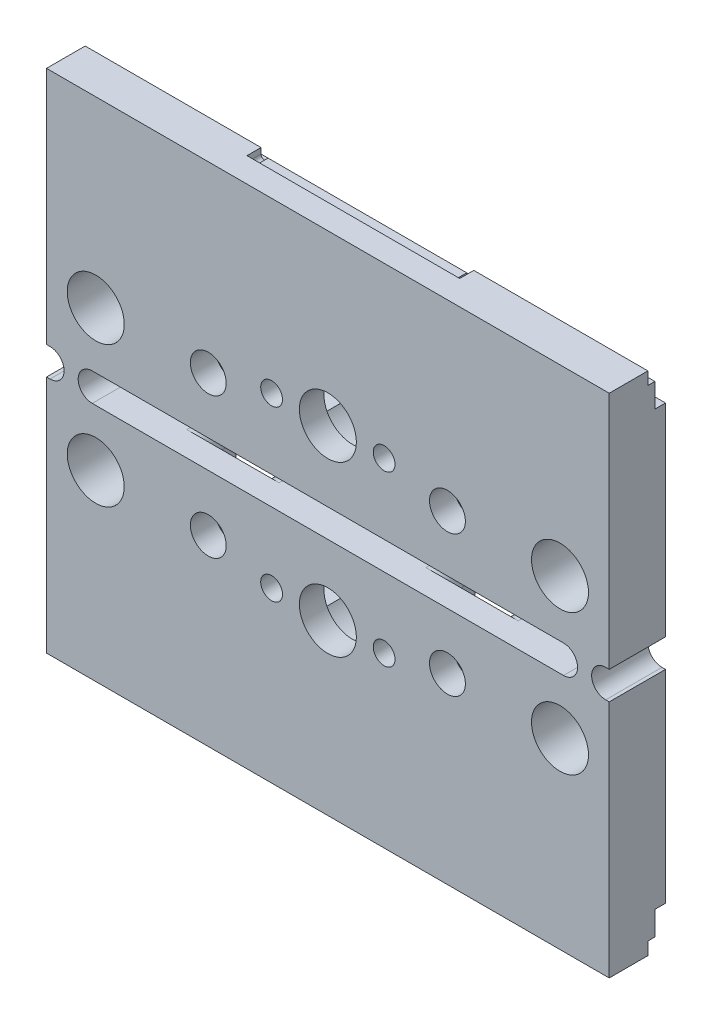
SolidWorks part; units mm, degrees
ref_plane "前视基准面" through (0, 0, 0) normal (0, 0, 1) x (1, 0, 0)
ref_plane "上视基准面" through (0, 0, 0) normal (0, 1, 0) x (1, 0, 0)
ref_plane "右视基准面" through (0, 0, 0) normal (1, 0, 0) x (0, 0, -1)
sketch "前视图草图" plane through (0, 0, 0) normal (0, 0, 1) x (1, 0, 0)
  line L0 (0, 0) -> (8.5179, 0) construction
  line L1 (0, 0) -> (0, 5.4227) construction
sketch "草图2" plane through (0, 0, 0) normal (0, 0, 1) x (1, 0, 0)
  line L0 (0, 0) -> (80, 0)
  line L1 (-200000, 0) -> (200008.5179, 0) construction
  line L2 (80, 0) -> (80, 34)
  line L3 (80, 34) -> (0, 34)
  line L4 (0, -200000) -> (0, 200005.4227) construction
  line L5 (0, 34) -> (0, 0)
  circle A0 centre (7, 8) radius 4.05
  circle A1 centre (40, 10) radius 4.05
  circle A2 centre (73, 8) radius 4.05
  dimension "D3" = 8
  dimension "D5" = 10
  dimension "D9" = 8.1
  dimension "D10" = 8.1
  dimension "D11" = 8.1
  dimension "D1" = 34
  dimension "D2" = 80
  dimension "D4" = 7
  dimension "D6" = 7
  dimension "D7" = 8
  dimension "D8" = 40
extrude "凸台-拉伸1" add sketch "草图2" along normal blind 8
sketch "草图3" plane through (0, 0, 8) normal (0, 0, 1) x (1, 0, 0)
  line L0 (16.088, 8) -> (31.4805, 8) construction
  line L1 (7, 8) -> (7, 16.8386) construction
  line L2 (73, 8) -> (73, 16.5917) construction
  line L4 (-200000, 0) -> (200008.5179, 0) construction
  circle A2 centre (23, 8) radius 2.55
  circle A3 centre (57, 8) radius 2.55
  dimension "D4" = 5.1
  dimension "D5" = 5.1
  dimension "D1" = 8
  dimension "D2" = 16
  dimension "D3" = 16
extrude "切除-拉伸1" cut sketch "草图3" against normal through all
sketch "草图4" plane through (80, 0, 0) normal (1, 0, 0) x (0, 0, -1)
  line L1 (0, -200000) -> (0, 200005.4227) construction
  line L2 (-1.5, 32.2) -> (-2.5, 32.2)
  line L3 (-2.5, 32.2) -> (-2.5, 34)
  line L4 (-8, 34) -> (0, 34) construction
  line L5 (-2.5, 34) -> (0, 34)
  line L6 (-1.5, 32.2) -> (-1.5, 28.8)
  line L7 (-1.5, 28.8) -> (0, 28.8)
  line L8 (0, 28.8) -> (0, 34)
  dimension "D1" = 3.4
  dimension "D2" = 2.5
  dimension "D3" = 1.5
  dimension "D4" = 1.8
extrude "切除-拉伸2" cut sketch "草图4" against normal through all
sketch "草图5" plane through (0, 0, 8) normal (0, 0, 1) x (1, 0, 0)
  line L0 (40, 10) -> (56.5376, 10) construction
  circle A0 centre (40, 10) radius 8 construction
  circle A1 centre (48, 10) radius 1.55
  circle A2 centre (32, 10) radius 1.55
  dimension "D1" = 3.1
  dimension "D2" = 3.1
  dimension "D3" = 16
extrude "切除-拉伸3" cut sketch "草图5" against normal through all
sketch "草图7" plane through (0, 0, 0) normal (0, 0, -1) x (-1, 0, 0)
  line L0 (-40, 12) -> (-40, -8.3696) construction
  line L1 (-23, 10) -> (-23, -2.3368) construction
  line L2 (200000, 0) -> (-200008.5179, 0) construction
  line L6 (-27.05, 10) -> (-27.05, 2.5)
  line L7 (-29.55, 0) -> (-16.45, 0)
  line L8 (-18.95, 2.5) -> (-18.95, 10)
  line L9 (-23, 8) -> (-23, 15.9045) construction
  line L13 (0, -200000) -> (0, 200005.4227) construction
  line L14 (-57, 8) -> (-57, 15.9045) construction
  line L15 (-57, 10) -> (-57, -2.3368) construction
  line L16 (-61.05, 2.5) -> (-61.05, 10)
  line L17 (-50.45, 0) -> (-63.55, 0)
  line L18 (-52.95, 10) -> (-52.95, 2.5)
  arc A1 (-18.95, 10) -> (-27.05, 10) centre (-23, 10) ccw
  arc A4 (-29.55, 0) -> (-27.05, 2.5) centre (-29.55, 2.5) ccw
  arc A5 (-18.95, 2.5) -> (-16.45, 0) centre (-16.45, 2.5) ccw
  arc A7 (-61.05, 2.5) -> (-63.55, 0) centre (-63.55, 2.5) cw
  arc A8 (-50.45, 0) -> (-52.95, 2.5) centre (-50.45, 2.5) cw
  arc A9 (-61.05, 10) -> (-52.95, 10) centre (-57, 10) cw
  dimension "D1" = 40
  dimension "D4" = 8.1
  dimension "D7" = 2.5
  dimension "D8" = 2.5
  dimension "D3" = 10
extrude "切除-拉伸4" cut sketch "草图7" against normal blind 4.5
sketch "草图8" plane through (0, 0, 0) normal (0, 0, -1) x (-1, 0, 0)
  line L0 (-40, 10) -> (-57.3165, 10) construction
  line L1 (-40, 20) -> (-40, 35.6562) construction
  line L2 (-30.5, 12.85) -> (-49.5, 12.85)
  line L3 (-49.5, 7.15) -> (-30.5, 7.15)
  line L4 (200000, 0) -> (-200008.5179, 0) construction
  arc A0 (-30.5, 7.15) -> (-30.5, 12.85) centre (-30.5, 10) ccw
  arc A1 (-49.5, 12.85) -> (-49.5, 7.15) centre (-49.5, 10) ccw
  dimension "D1" = 5.7
  dimension "D2" = 9.5
  dimension "D3" = 9.5
  dimension "D4" = 10
extrude "切除-拉伸5" cut sketch "草图8" against normal blind 4.5
sketch "草图20" plane through (0, 0, 0) normal (0, 0, -1) x (-1, 0, 0)
  circle A0 centre (-40, 10) radius 5.5
  dimension "D1" = 11
extrude "切除-拉伸12" cut sketch "草图20" against normal blind 4.5
sketch "草图19" plane through (0, 0, 2.5) normal (0, 0, -1) x (-1, 0, 0)
  line L0 (0, 34) -> (-80, 34) construction
  line L1 (-25, 34) -> (-55.2479, 34)
  line L2 (-25, 34) -> (-25, 33.2)
  line L3 (-26, 33.2) -> (-54.2479, 33.2)
  line L4 (-55.2479, 34) -> (-55.2479, 33.2)
  line L5 (0, -200000) -> (0, 200005.4227) construction
  line L7 (0, 32.2) -> (-80, 32.2) construction
  line L8 (-56.3335, 32.7) -> (-52.9089, 32.7) construction
  line L9 (-55.2479, 1028.5823) -> (-55.2479, 33.2) construction
  line L10 (-25, 1028.5823) -> (-25, 32.7) construction
  line L11 (-55.2479, 32.7) -> (-55.2479, -973.3) construction
  line L12 (-25, 32.7) -> (-25, -973.3) construction
  arc A3 (-55.2479, 33.2) -> (-54.2479, 33.2) centre (-54.7479, 33.2) ccw
  arc A6 (-26, 33.2) -> (-25, 33.2) centre (-25.5, 33.2) ccw
  dimension "D3" = 1
  dimension "D4" = 1
  dimension "D2" = 0.8
  dimension "D1" = 0.5
  dimension "D9" = 25
extrude "切除-拉伸11" cut sketch "草图19" against normal blind 2
sketch "草图22" plane through (0, 0, 8) normal (0, 0, 1) x (1, 0, 0)
  line L1 (0, -200000) -> (0, 200005.4227) construction
  line L2 (0.5, -4) -> (6.5, -4)
  line L4 (79.5, 0) -> (73.5, 0)
  line L5 (4.5, 1.9875) -> (4.5, -4.1402) construction
  line L6 (75.5, -11.5647) -> (75.5, -5.1636) construction
  line L7 (80, 0) -> (80, 34) construction
  line L8 (73.5, -4) -> (79.5, -4)
  line L9 (6.5, 0) -> (0.5, 0)
  line L10 (77.5, -2.9635) -> (77.5, -4.3032) construction
  line L11 (2.5, -8.393) -> (2.5, -15.1693) construction
  arc A0 (6.5, 0) -> (6.5, -4) centre (6.5, -2) ccw
  arc A1 (73.5, -4) -> (73.5, 0) centre (73.5, -2) ccw
  arc A2 (0.5, -4) -> (0.5, 0) centre (0.5, -2) ccw
  arc A3 (79.5, 0) -> (79.5, -4) centre (79.5, -2) ccw
  dimension "D1" = 4.5
  dimension "D2" = 4.5
  dimension "D3" = 4
  dimension "D4" = 2.5
  dimension "D5" = 2.5
extrude "凸台-拉伸2" add sketch "草图22" against normal blind 8
ref_plane "基准面1" through (0, -2, 0) normal (0, -1, 0) x (-1, 0, 0)
mirror "镜向2" about plane through (0, -2, 0) normal (0, -1, 0) of "凸台-拉伸1", "切除-拉伸1", "切除-拉伸2", "切除-拉伸3", "切除-拉伸4", "切除-拉伸5", "切除-拉伸12", "切除-拉伸11"
